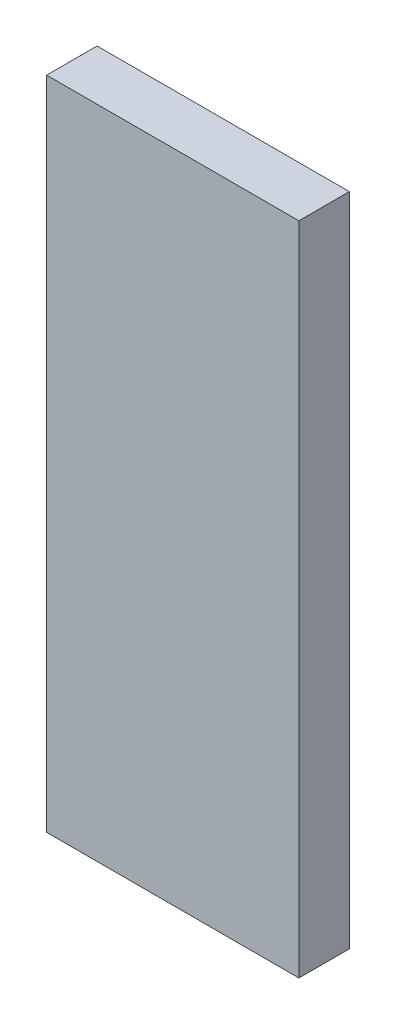
SolidWorks part; units mm, degrees
ref_plane "前视基准面" through (0, 0, 0) normal (0, 0, 1) x (1, 0, 0)
ref_plane "上视基准面" through (0, 0, 0) normal (0, 1, 0) x (1, 0, 0)
ref_plane "右视基准面" through (0, 0, 0) normal (1, 0, 0) x (0, 0, -1)
other "Configuration Table"
sketch "草图1" plane through (0, 0, 0) normal (0, 1, 0) x (1, 0, 0)
  line L1 (12.5, -2.5) -> (-12.5, -2.5)
  line L2 (12.5, -2.5) -> (12.5, 2.5)
  line L3 (12.5, 2.5) -> (-12.5, 2.5)
  line L4 (-12.5, -2.5) -> (-12.5, 2.5)
  line L5 (12.5, -2.5) -> (-12.5, 2.5) construction
  line L6 (12.5, 2.5) -> (-12.5, -2.5) construction
  point P0 (0, 0)
  dimension "D1" = 25
  dimension "D2" = 5
extrude "凸台-拉伸1" add sketch "草图1" along normal blind 65
sketch "草图2" plane through (0, 65, 0) normal (0, 1, 0) x (1, 0, 0)
  circle A0 centre (0, 0) radius 4.6989
